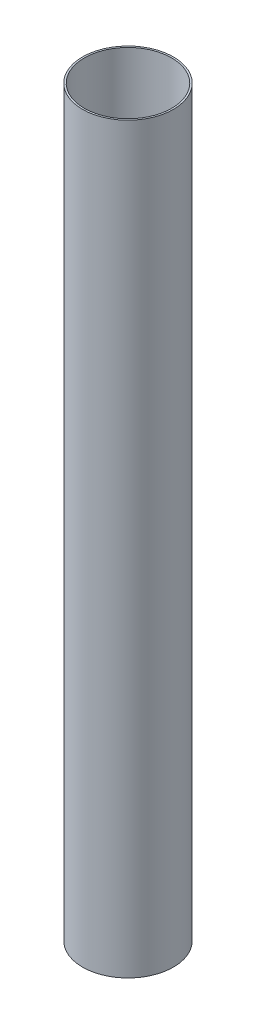
SolidWorks part; units mm, degrees
material "A-Glass Fiber"
ref_plane "Front Plane" through (0, 0, 0) normal (0, 0, 1) x (1, 0, 0)
ref_plane "Top Plane" through (0, 0, 0) normal (0, 1, 0) x (1, 0, 0)
ref_plane "Right Plane" through (0, 0, 0) normal (1, 0, 0) x (0, 0, -1)
sketch "Sketch1" plane through (0, 0, 0) normal (0, 1, 0) x (1, 0, 0)
  circle A0 centre (0, 0) radius 38.1
  circle A1 centre (0, 0) radius 39.624
  dimension "D1" = 76.2
  dimension "D2" = 79.248
extrude "Boss-Extrude1" add sketch "Sketch1" along normal blind 647.7 contours A1 A0
